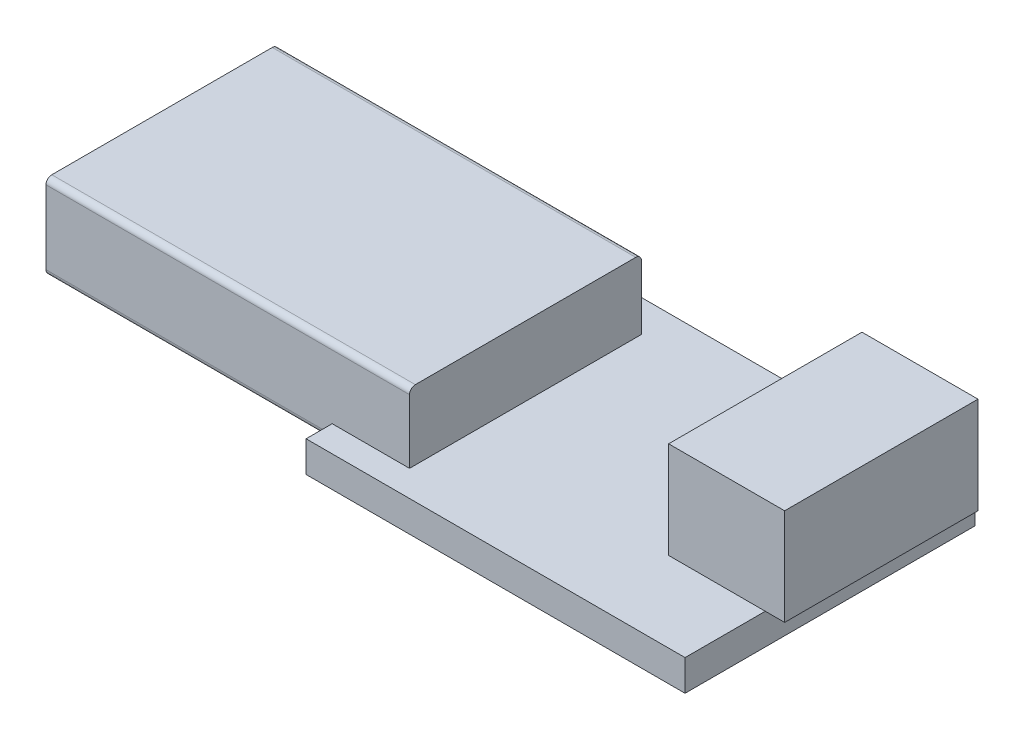
SolidWorks part; units mm, degrees
ref_plane "Front Plane" through (0, 0, 0) normal (0, 0, 1) x (1, 0, 0)
ref_plane "Top Plane" through (0, 0, 0) normal (0, 1, 0) x (1, 0, 0)
ref_plane "Right Plane" through (0, 0, 0) normal (1, 0, 0) x (0, 0, -1)
sketch "Sketch1" plane through (0, 0, 0) normal (0, 1, 0) x (1, 0, 0)
  line L1 (-9.8, -7.5) -> (9.8, -7.5)
  line L2 (-9.8, -7.5) -> (-9.8, 7.5)
  line L3 (-9.8, 7.5) -> (9.8, 7.5)
  line L4 (9.8, -7.5) -> (9.8, 7.5)
  line L5 (-9.8, -7.5) -> (9.8, 7.5) construction
  line L6 (-9.8, 7.5) -> (9.8, -7.5) construction
  point P0 (0, 0)
  dimension "D1" = 15
  dimension "D2" = 19.6
extrude "Boss-Extrude1" add sketch "Sketch1" along normal mid plane 1.6
sketch "Sketch2" plane through (0, 0, 0) normal (0, 1, 0) x (1, 0, 0)
  line L0 (-9.8, 7.5) -> (-9.8, -7.5) construction
  line L1 (-24.6, 5.85) -> (-5.8, 5.85)
  line L2 (-24.6, 5.85) -> (-24.6, -6.15)
  line L3 (-24.6, -6.15) -> (-5.8, -6.15)
  line L4 (-5.8, 5.85) -> (-5.8, -6.15)
  line L5 (-9.8, -7.5) -> (9.8, -7.5) construction
  dimension "D1" = 12
  dimension "D2" = 18.8
  dimension "D3" = 14.8
  dimension "D4" = 1.35
extrude "Boss-Extrude2" add sketch "Sketch2" along normal blind 4.4
sketch "Sketch3" plane through (-24.6, 0, 0) normal (-1, 0, 0) x (0, 0, 1)
  line L8 (5.85, 0.3) -> (5.85, 4.1)
  line L9 (5.85, 4.1) -> (-5.55, 4.1)
  line L10 (-5.55, 4.1) -> (-5.55, 0.3)
  line L11 (-5.55, 0.3) -> (5.85, 0.3)
  line L12 (5.85, 0.3) -> (5.85, 4.1)
  line L13 (5.85, 4.1) -> (-5.55, 4.1)
  line L14 (-5.55, 4.1) -> (-5.55, 0.3)
  line L15 (-5.55, 0.3) -> (5.85, 0.3)
  dimension "D1" = 0.3
extrude "Cut-Extrude1" cut sketch "Sketch3" against normal offset from surface (16.8 mm away) 2 up to face at (-5.8, 2.6, 0.15)
fillet "Fillet1" radius 0.3 8 edges at (-17.2, 0, -5.85) (-15.2, 4.4, -5.85) (-17.2, 0, 6.15) (-15.2, 4.4, 6.15) (-16.2, 0.3, 5.85) (-16.2, 4.1, 5.85) (-16.2, 4.1, -5.55) (-16.2, 0.3, -5.55)
sketch "Sketch4" plane through (0, 0.8, 0) normal (0, 1, 0) x (1, 0, 0)
  line L0 (9.8, -7.5) -> (9.8, 7.5) construction
  line L1 (10.8, 6.65) -> (4.8, 6.65)
  line L2 (10.8, 6.65) -> (10.8, -3.35)
  line L3 (10.8, -3.35) -> (4.8, -3.35)
  line L4 (4.8, 6.65) -> (4.8, -3.35)
  line L5 (9.8, 7.5) -> (-9.8, 7.5) construction
  dimension "D1" = 10
  dimension "D2" = 6
  dimension "D3" = 1
  dimension "D4" = 0.85
extrude "Boss-Extrude3" add sketch "Sketch4" along normal blind 5
sketch "Sketch5" plane through (-7.8, 0, 0) normal (-1, 0, 0) x (0, 0, 1)
  line L0 (5.55, 0.3) -> (-5.25, 0.3) construction
  line L1 (5.55, 0.3) -> (-5.25, 0.3)
  line L2 (-5.55, 0.6) -> (-5.55, 2.3)
  line L3 (-5.55, 0.6) -> (-5.55, 3.8) construction
  line L4 (-5.55, 2.3) -> (5.85, 2.3)
  line L5 (5.85, 3.8) -> (5.85, 0.6) construction
  line L6 (5.85, 2.3) -> (5.85, 0.6)
  arc A0 (5.55, 0.3) -> (5.85, 0.6) centre (5.55, 0.6) ccw construction
  arc A1 (-5.55, 0.6) -> (-5.25, 0.3) centre (-5.25, 0.6) ccw construction
  arc A2 (5.55, 0.3) -> (5.85, 0.6) centre (5.55, 0.6) ccw
  arc A3 (-5.55, 0.6) -> (-5.25, 0.3) centre (-5.25, 0.6) ccw
  dimension "D1" = 2
extrude "Boss-Extrude4" add sketch "Sketch5" along normal offset from surface (16.7 mm away) 0.1 up to face at (-24.6, 2.2, 0.15)
